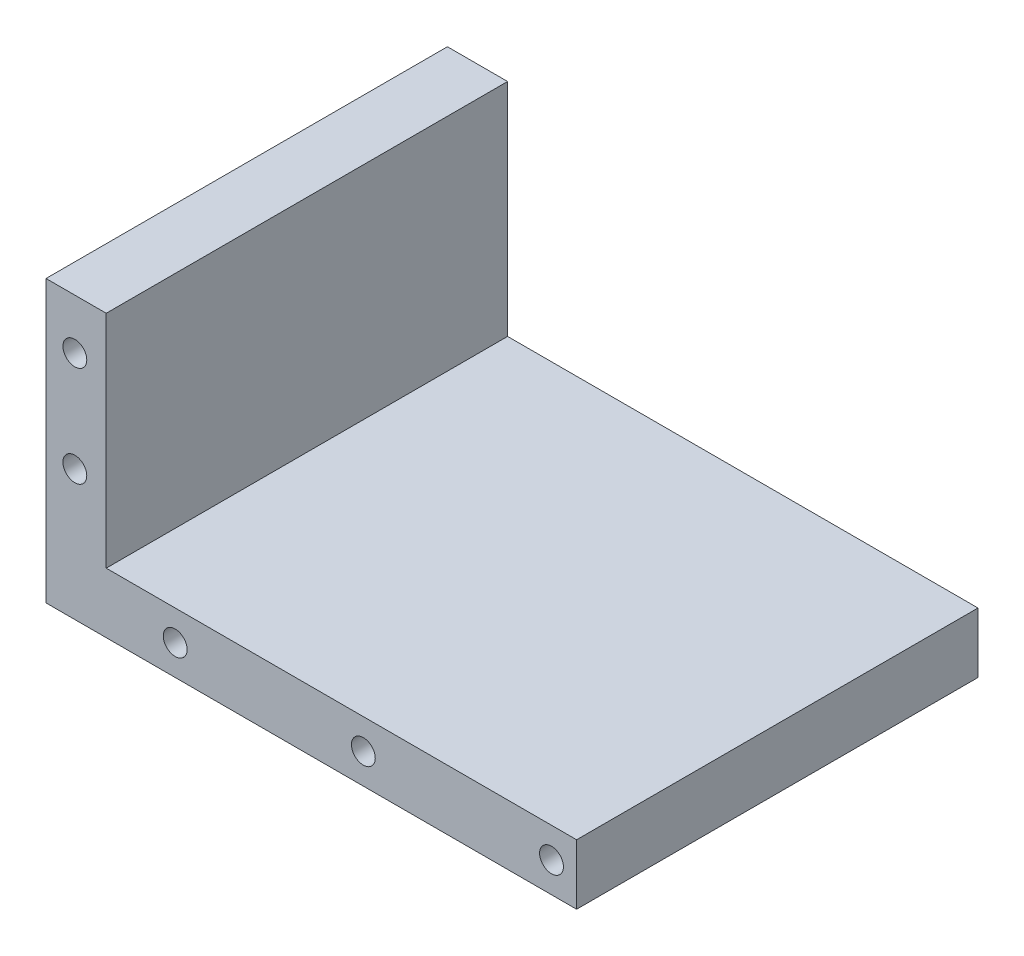
SolidWorks part; units mm, degrees
ref_plane "前视基准面" through (0, 0, 0) normal (0, 0, 1) x (1, 0, 0)
ref_plane "上视基准面" through (0, 0, 0) normal (0, 1, 0) x (1, 0, 0)
ref_plane "右视基准面" through (0, 0, 0) normal (1, 0, 0) x (0, 0, -1)
sketch "草图1" plane through (0, 0, 0) normal (0, 0, 1) x (1, 0, 0)
  line L0 (0, 17.6) -> (0, 0)
  line L1 (0, 0) -> (37.5, 0)
  line L2 (37.5, 0) -> (37.5, -4.8)
  line L3 (37.5, -4.8) -> (-4.8, -4.8)
  line L4 (-4.8, -4.8) -> (-4.8, 17.6)
  line L5 (-4.8, 17.6) -> (0, 17.6)
  circle A0 centre (-2.5, 13.6) radius 0.95
  circle A1 centre (35.5, -2.4) radius 0.95
  circle A2 centre (20.5, -2.4) radius 0.95
  circle A3 centre (5.5, -2.4) radius 0.95
  circle A4 centre (-2.5, 5.6) radius 0.95
  dimension "D5" = 4
  dimension "D6" = 2
  dimension "D9" = 2.5
  dimension "D10" = 2.4
  dimension "D11" = 1.9
  dimension "D12" = 1.9
  dimension "D1" = 17.6
  dimension "D2" = 37.5
  dimension "D3" = 4.8
  dimension "D4" = 4.8
  dimension "D7" = 3
  dimension "D8" = 2
extrude "凸台-拉伸1" add sketch "草图1" along normal blind 32
